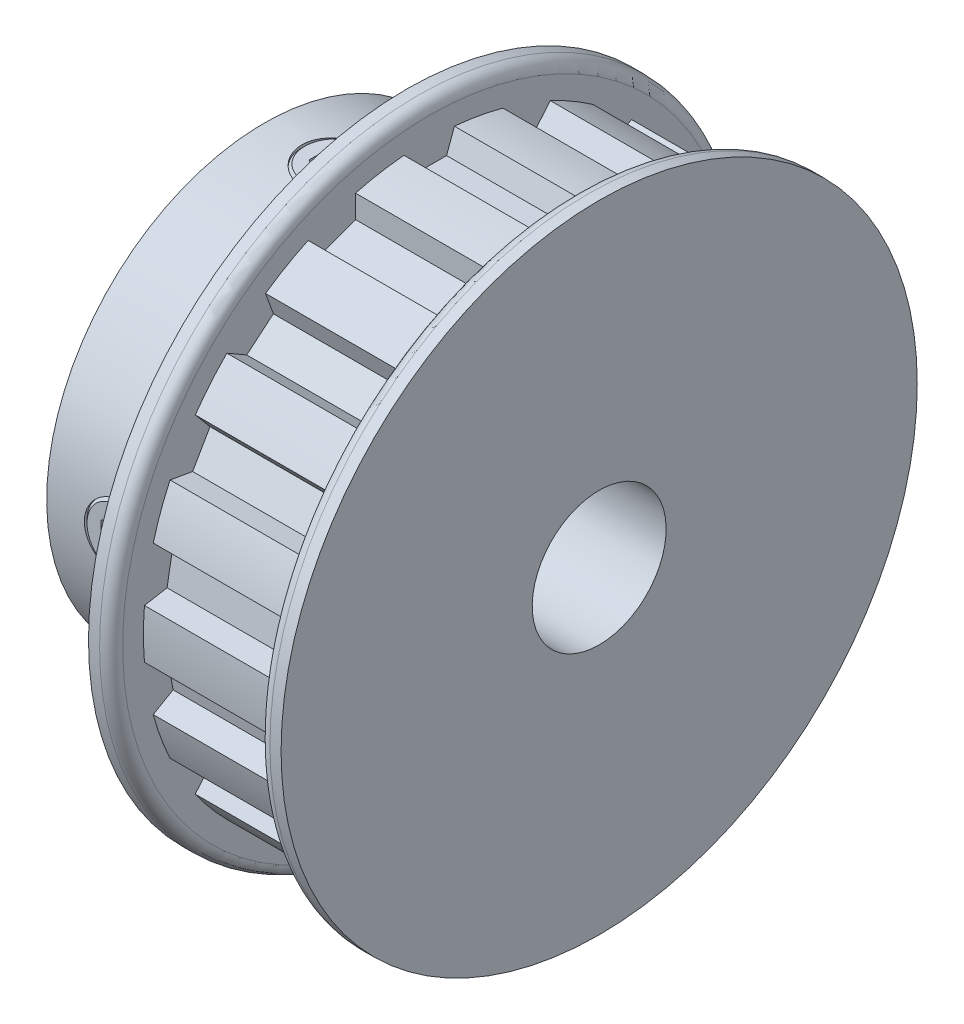
SolidWorks part; units mm, degrees
material "6061 Alloy"
ref_plane "Front Plane" through (0, 0, 0) normal (0, 0, 1) x (1, 0, 0)
ref_plane "Top Plane" through (0, 0, 0) normal (0, 1, 0) x (1, 0, 0)
ref_plane "Right Plane" through (0, 0, 0) normal (1, 0, 0) x (0, 0, -1)
sketch "Sketch2" plane through (0, 0, 0) normal (1, 0, 0) x (0, 0, -1)
  line L3 (0, 0) -> (0, 25.0052) construction
  line L6 (0, -26.9102) -> (0, -27.2923) construction
  line L7 (-2.3241, 26.8097) -> (-1.6476, 24.9509)
  line L8 (2.3241, 26.8097) -> (1.6476, 24.9509)
  line L9 (-2.3241, 26.8097) -> (-2.3917, 26.9955)
  line L10 (2.3241, 26.8097) -> (2.3917, 26.9955)
  line L12 (-1.6476, 24.9509) -> (1.6476, 24.9509)
  line L14 (0, 26.9102) -> (0, 27.2923) construction
  line L15 (0, 0) -> (0, -3.556) construction
  circle A0 centre (0, 0) radius 27.2923 construction
  circle A1 centre (0, 0) radius 25.0052 construction
  circle A2 centre (0, 0) radius 26.9102 construction
  arc A7 (2.3917, 26.9955) -> (-2.3917, 26.9955) centre (0, 0) ccw
  point P5 (0, 27.1013)
  dimension "D2" = 53.8204
  dimension "D1" = 40
sketch "Sketch1" plane through (0, 0, 0) normal (0, 0, 1) x (1, 0, 0)
  line L0 (-15.875, 0) -> (15.875, 0) construction
  line L1 (-15.875, 6.35) -> (15.875, 6.35)
  line L2 (-15.875, 6.35) -> (-15.875, 20.6375)
  line L3 (-2.3876, 30.1625) -> (-1.3335, 30.1625)
  line L4 (-0.2413, 27.2923) -> (-0.2413, 29.0703)
  line L5 (-0.2413, 30.8483) -> (-0.2413, 27.2923) construction
  line L6 (-0.2413, 27.2923) -> (13.7287, 27.2923)
  line L7 (13.7287, 27.2923) -> (13.7287, 29.0703)
  line L8 (13.7287, 27.2923) -> (15.875, 27.2923) construction
  line L9 (14.8209, 30.1625) -> (15.875, 30.1625)
  line L10 (15.875, 30.1625) -> (15.875, 6.35)
  line L11 (-2.3876, 20.6375) -> (15.875, 20.6375) construction
  line L12 (-9.1313, 20.6375) -> (-9.1313, 6.35) construction
  line L13 (-2.3876, 30.1625) -> (-2.3876, 20.6375)
  line L14 (-2.3876, 20.6375) -> (-15.875, 20.6375)
  line L15 (6.7437, 20.6375) -> (6.7437, 27.2923) construction
  arc A0 (13.7287, 29.0703) -> (14.8209, 30.1625) centre (14.8209, 29.0703) cw
  arc A1 (-0.2413, 29.0703) -> (-1.3335, 30.1625) centre (-1.3335, 29.0703) ccw
  dimension "Bore Size" = 12.7
  dimension "Overall Width" = 31.75
  dimension "Inside Width" = 13.97
  dimension "OD" = 60.325
  dimension "D2" = 54.5846
  dimension "D3" = 3.556
  dimension "D4" = 1.778
  dimension "Outside Width" = 18.2626
revolve "Revolve1" add sketch "Sketch1" angle 360 mid plane about L0
sketch "Sketch4" plane through (-0.2413, 0, 0) normal (1, 0, 0) x (0, 0, -1)
  circle A0 centre (0, 0) radius 27.1013
  circle A2 centre (0, 0) radius 27.2923
  circle A3 centre (0, 0) radius 27.2923 construction
extrude "Cut-Extrude2" cut sketch "Sketch4" along normal up to surface (13.97 mm away) up to face at (13.7287, -27.2923, 0)
sketch "Sketch3" plane through (-0.2413, 0, 0) normal (1, 0, 0) x (0, 0, -1)
  line L2 (-2.3241, 26.8097) -> (-1.6476, 24.9509) construction
  line L3 (-1.6476, 24.9509) -> (1.6476, 24.9509) construction
  line L4 (2.3241, 26.8097) -> (1.6476, 24.9509) construction
  line L5 (-2.3917, 26.9955) -> (-1.6476, 24.9509)
  line L6 (-1.6476, 24.9509) -> (1.6476, 24.9509)
  line L7 (2.3917, 26.9955) -> (1.6476, 24.9509)
  arc A1 (2.3917, 26.9955) -> (-2.3917, 26.9955) centre (0, 0) ccw construction
  arc A2 (2.3917, 26.9955) -> (-2.3917, 26.9955) centre (0, 0) ccw
extrude "Cut-Extrude1" cut sketch "Sketch3" along normal up to surface (13.97 mm away)
pattern_circular "CirPattern1" count 18 over 360 about axis through (0, 0, 0) along (1, 0, 0) of "Cut-Extrude1"
sketch "Sketch5" plane through (0, 0, 0) normal (0, 0, 1) x (1, 0, 0)
  line L1 (13.7287, 29.0703) -> (13.7287, -29.0703) construction
  point P0 (13.7287, 0)
sketch "Sketch6" plane through (0, 0, 0) normal (0, 1, 0) x (1, 0, 0)
  line L0 (-15.875, 0) -> (-12.3063, 0) construction
  line L1 (-15.875, 30.1625) -> (-15.875, -30.1625) construction
  line L2 (-2.3876, 0) -> (-5.9563, 0) construction
  line L4 (-2.3876, 30.1625) -> (-2.3876, -30.1625) construction
  circle A0 centre (-9.1313, 0) radius 3.175
  dimension "D1" = 6.35
extrude "Cut-Extrude3" cut sketch "Sketch6" along normal through all
sketch "Sketch7" plane through (0, 0, 0) normal (0, 0, 1) x (1, 0, 0)
  line L0 (-12.0523, 20.6375) -> (-9.1313, 20.6375)
  line L1 (-12.3063, 20.3835) -> (-12.3063, 6.985)
  line L2 (-12.3063, 6.985) -> (-12.0523, 6.731)
  line L3 (-12.0523, 6.731) -> (-9.1313, 6.731)
  line L4 (-9.1313, 6.731) -> (-9.1313, 20.6375) construction
  line L5 (-2.3876, 20.6375) -> (-15.875, 20.6375) construction
  line L6 (-12.3063, 20.3835) -> (-12.0523, 20.6375)
  line L8 (-9.1313, 20.6375) -> (-9.1313, 6.731)
  point P0 (-12.3063, 20.6375)
  point P4 (-12.3063, 6.731)
  dimension "D1" = 6.35
  dimension "D2" = 0.381
revolve "Revolve2" add sketch "Sketch7" angle 360 mid plane about L4
sketch "Sketch8" plane through (0, 20.6375, 0) normal (0, 1, 0) x (1, 0, 0)
  line L1 (-9.1313, 1.8331) -> (-10.7188, 0.9165)
  line L2 (-10.7188, 0.9165) -> (-10.7188, -0.9165)
  line L3 (-10.7188, -0.9165) -> (-9.1313, -1.8331)
  line L4 (-9.1313, -1.8331) -> (-7.5438, -0.9165)
  line L5 (-7.5438, -0.9165) -> (-7.5438, 0.9165)
  line L6 (-7.5438, 0.9165) -> (-9.1313, 1.8331)
  circle A0 centre (-9.1313, 0) radius 1.5875 construction
  dimension "D1" = 3.175
extrude "Cut-Extrude4" cut sketch "Sketch8" against normal blind 2.032
pattern_circular "CirPattern2" count 2 over 90 about axis through (-15.875, 0, 0) along (-1, 0, 0) of "Cut-Extrude3"
pattern_circular "CirPattern3" count 2 over 90 about axis through (0, 0, 0) along (1, 0, 0) of bodies 107
equation "\"D2@Sketch1\" = \"PD@Sketch2\""
equation "\"D3@Sketch1\" = \"hs@Sketch2\""
equation "\"D4@Sketch1\" = \"D3@Sketch1\"/2"
equation "\"D2@Sketch2\" = \"PD@Sketch2\"*.986"
